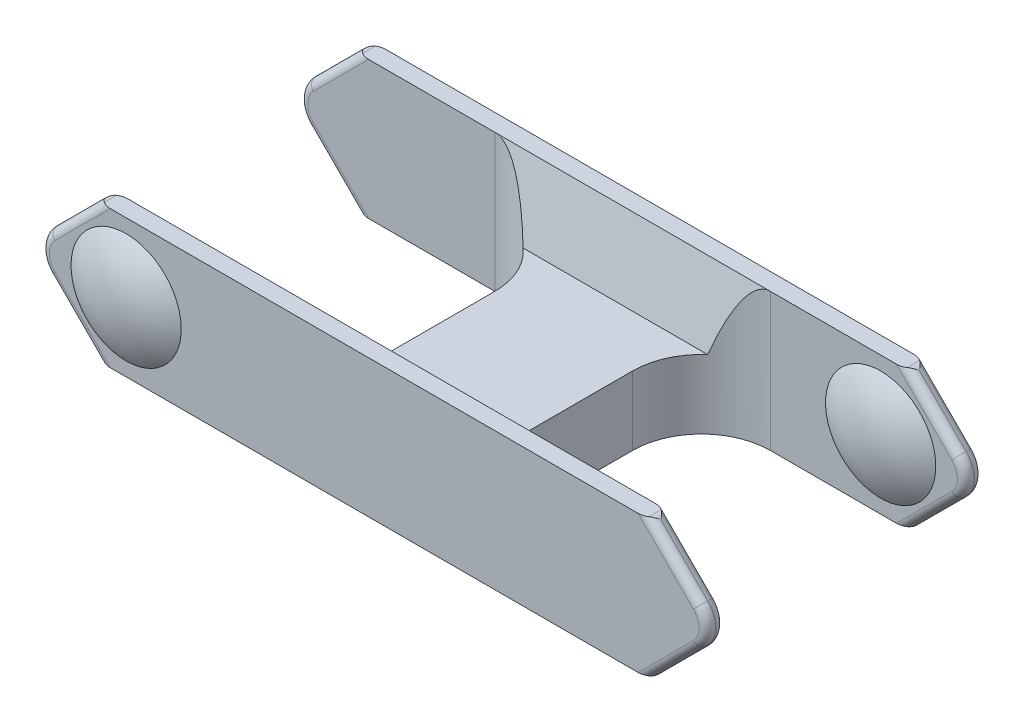
SolidWorks part; units mm, degrees
ref_plane "Front Plane" through (0, 0, 0) normal (0, 0, 1) x (1, 0, 0)
ref_plane "Top Plane" through (0, 0, 0) normal (0, 1, 0) x (1, 0, 0)
ref_plane "Right Plane" through (0, 0, 0) normal (1, 0, 0) x (0, 0, -1)
sketch "Sketch1" plane through (0, 0, 0) normal (0, 1, 0) x (1, 0, 0)
  line L0 (-6.35, 12.7) -> (-6.35, -12.7) construction
  line L1 (-31.75, -12.7) -> (31.75, -12.7)
  line L2 (-31.75, -12.7) -> (-31.75, -11.1125)
  line L3 (-31.75, 12.7) -> (31.75, 12.7)
  line L5 (-31.75, -12.7) -> (31.75, 12.7) construction
  line L6 (-31.75, 12.7) -> (31.75, -12.7) construction
  line L7 (-31.75, 11.1125) -> (-12.7, 11.1125)
  line L8 (-6.35, 4.7625) -> (-6.35, -4.7625)
  line L9 (-12.7, -11.1125) -> (-31.75, -11.1125)
  line L10 (-31.75, 11.1125) -> (-31.75, 12.7)
  line L11 (0, 0) -> (0, 12.7) construction
  line L12 (31.75, 12.7) -> (31.75, 11.1125)
  line L13 (31.75, -12.7) -> (31.75, -11.1125)
  line L14 (12.7, -11.1125) -> (31.75, -11.1125)
  line L15 (6.35, 4.7625) -> (6.35, -4.7625)
  line L16 (31.75, 11.1125) -> (12.7, 11.1125)
  arc A0 (-6.35, -4.7625) -> (-12.7, -11.1125) centre (-12.7, -4.7625) cw
  arc A1 (-12.7, 11.1125) -> (-6.35, 4.7625) centre (-12.7, 4.7625) cw
  arc A2 (6.35, -4.7625) -> (12.7, -11.1125) centre (12.7, -4.7625) ccw
  arc A3 (12.7, 11.1125) -> (6.35, 4.7625) centre (12.7, 4.7625) ccw
  point P0 (0, 0)
  point P14 (-6.35, -11.1125)
  point P17 (-6.35, 11.1125)
  dimension "D6" = 6.35
  dimension "D1" = 63.5
  dimension "D2" = 25.4
  dimension "D3" = 25.4
  dimension "D4" = 1.5875
  dimension "D5" = 1.5875
extrude "Boss-Extrude1" add sketch "Sketch1" along normal blind 12.7
sketch "Sketch3" plane through (-31.75, 0, 0) normal (-1, 0, 0) x (0, 0, 1)
  line L7 (11.1125, 12.7) -> (4.7625, 12.7) construction
  line L8 (-4.7625, 12.7) -> (4.7625, 12.7) construction
  line L9 (-4.7625, 12.7) -> (-11.1125, 12.7) construction
  line L19 (11.1125, 12.7) -> (4.7625, 12.7)
  line L20 (-4.7625, 12.7) -> (4.7625, 12.7)
  line L21 (-4.7625, 12.7) -> (-11.1125, 12.7)
  line L24 (0, 0) -> (0, 12.7) construction
  line L25 (-12.7, 6.35) -> (12.7, 6.35) construction
  line L26 (-9.525, 6.35) -> (9.525, 6.35)
  line L27 (-11.1125, 12.7) -> (-9.525, 6.35)
  line L28 (9.525, 6.35) -> (11.1125, 12.7)
  point P17 (0, 6.35)
  dimension "D1" = 19.05
  dimension "D2" = 6.35
extrude "Cut-Extrude2" cut sketch "Sketch3" against normal through all
sketch "Sketch2" plane through (0, 0, 12.7) normal (0, 0, 1) x (1, 0, 0)
  line L0 (-29.9539, 8.1461) -> (-25.4, 12.7)
  line L1 (-29.9539, 4.5539) -> (-25.4, 0)
  line L3 (0, 0) -> (0, 12.7) construction
  line L4 (-31.75, 0) -> (31.75, 0)
  line L5 (31.75, 0) -> (31.75, 12.7)
  line L6 (31.75, 12.7) -> (-31.75, 12.7)
  line L7 (-31.75, 12.7) -> (-31.75, 0)
  line L8 (-31.75, 0) -> (-25.4, 0)
  line L9 (31.75, 0) -> (31.75, 12.7)
  line L10 (31.75, 12.7) -> (25.4, 12.7)
  line L11 (-31.75, 12.7) -> (-31.75, 0)
  line L13 (29.9539, 4.5539) -> (25.4, 0)
  line L14 (29.9539, 8.1461) -> (25.4, 12.7)
  line L15 (31.75, 12.7) -> (31.75, 0)
  line L16 (-31.75, 0) -> (-31.75, 12.7)
  line L17 (-31.75, 6.35) -> (31.75, 6.35) construction
  line L21 (-25.4, 12.7) -> (-31.75, 12.7)
  line L22 (25.4, 0) -> (31.75, 0)
  arc A0 (29.9539, 4.5539) -> (29.9539, 8.1461) centre (28.1579, 6.35) ccw
  arc A1 (-29.9539, 8.1461) -> (-29.9539, 4.5539) centre (-28.1579, 6.35) ccw
  line M12 (-31.75, 0) -> (31.75, 0)
  line M13 (31.75, 0) -> (31.75, 12.7)
  line M14 (31.75, 12.7) -> (-31.75, 12.7)
  line M15 (-31.75, 12.7) -> (-31.75, 0)
  dimension "D4" = 2.54
  dimension "D2" = 45
  dimension "D3" = 45
  dimension "D1" = 0
extrude "Cut-Extrude1" cut sketch "Sketch2" against normal through all contours A1 L0 L1 M14 M15 M12 | A0 L13 L14 M12 M13 M14
ref_plane "Plane1" through (-22.86, 0, 0) normal (-1, 0, 0) x (0, 0, 1)
sketch "Sketch4" plane through (-22.86, 0, 0) normal (-1, 0, 0) x (0, 0, 1)
  line L0 (0, 6.35) -> (14.2875, 6.35) construction
  line L1 (4.7625, 6.35) -> (-4.7625, 6.35) construction
  line L2 (12.7, 6.35) -> (12.7, 11.43)
  line L3 (12.7, 8.1461) -> (12.7, 12.7) construction
  line L4 (12.7, 6.35) -> (14.2875, 6.35)
  arc A0 (12.7, 11.43) -> (14.2875, 6.35) centre (5.3657, 6.35) cw
  dimension "D3" = 8.9217
  dimension "D1" = 5.08
  dimension "D2" = 1.5875
revolve "Revolve1" add sketch "Sketch4" angle 360 about L0
ref_plane "Plane2" through (0, 0, 0) normal (0, 0, 1) x (1, 0, 0)
mirror "Mirror1" about plane through (0, 0, 0) normal (0, 0, 1) of "Revolve1"
ref_plane "Plane3" through (22.86, 0, 0) normal (1, 0, 0) x (0, 0, -1)
sketch "Sketch5" plane through (22.86, 0, 0) normal (1, 0, 0) x (0, 0, -1)
  line L0 (9.525, 6.35) -> (0, 6.35) construction
  line L2 (11.1125, 6.35) -> (11.1125, 11.43)
  line L3 (11.1125, 12.7) -> (11.1125, 0) construction
  line L4 (11.1125, 12.7) -> (11.1125, 8.1461) construction
  line L5 (11.1125, 6.35) -> (9.525, 6.35)
  line L6 (4.7625, 6.35) -> (-4.7625, 6.35) construction
  arc A0 (11.1125, 11.43) -> (9.525, 6.35) centre (18.4467, 6.35) ccw
  dimension "D3" = 8.9217
  dimension "D1" = 5.08
  dimension "D2" = 1.5875
revolve "Revolve2" add sketch "Sketch5" angle 360 about L0
mirror "Mirror2" about plane through (0, 0, 0) normal (0, 0, 1) of "Revolve2"
ref_plane "Plane4" through (0, 0, 0) normal (1, 0, 0) x (0, 0, -1)
fillet "Fillet1" radius 0.762 28 edges at (-27.677, 2.277, 11.1125) (-30.6979, 6.35, 11.1125) (-27.677, 2.277, 12.7) (-30.6979, 6.35, 12.7) (-27.677, 2.277, -11.1125) (-30.6979, 6.35, -11.1125) (-27.677, 2.277, -12.7) (-30.6979, 6.35, -12.7) (27.677, 2.277, -12.7) (30.6979, 6.35, -12.7) (27.677, 2.277, -11.1125) (30.6979, 6.35, -11.1125) (27.677, 2.277, 12.7) (30.6979, 6.35, 12.7) (27.677, 2.277, 11.1125) (30.6979, 6.35, 11.1125) (-27.677, 10.423, 11.1125) (-25.4, 12.7, 11.9063) (-27.677, 10.423, 12.7) (-27.677, 10.423, -11.1125) (-27.677, 10.423, -12.7) (-25.4, 12.7, -11.9062) (25.4, 12.7, -11.9062) (27.677, 10.423, -12.7) (27.677, 10.423, -11.1125) (27.677, 10.423, 12.7) (25.4, 12.7, 11.9063) (27.677, 10.423, 11.1125)
